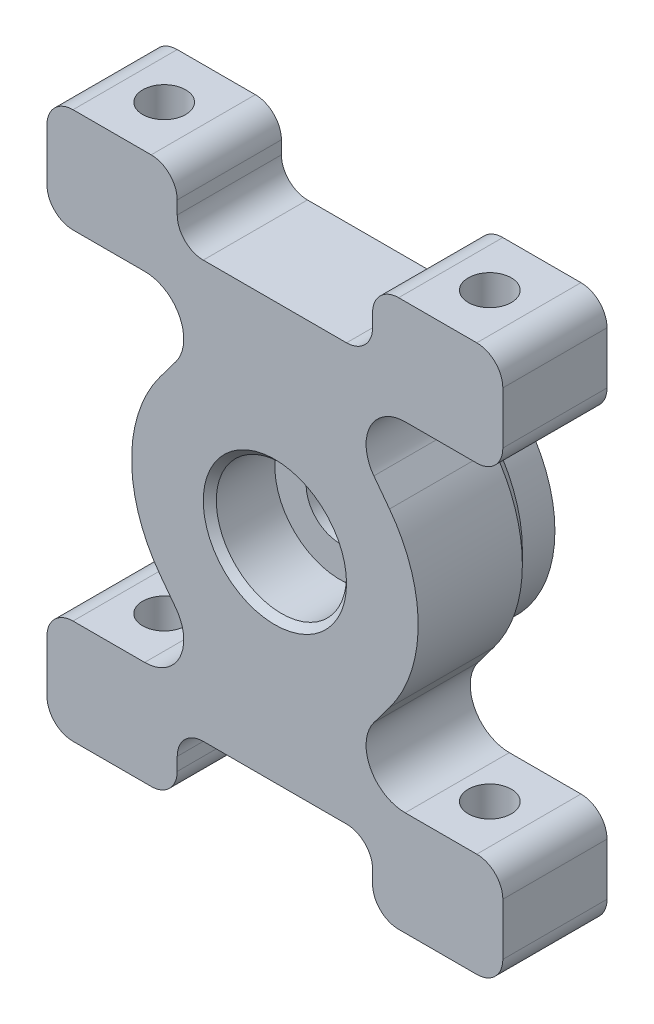
SolidWorks part; units mm, degrees
material "6061 合金"
ref_plane "前视基准面" through (0, 0, 0) normal (0, 0, 1) x (1, 0, 0)
ref_plane "上视基准面" through (0, 0, 0) normal (0, 1, 0) x (1, 0, 0)
ref_plane "右视基准面" through (0, 0, 0) normal (1, 0, 0) x (0, 0, -1)
sketch "草图1" plane through (0, 0, 0) normal (0, 0, 1) x (1, 0, 0)
  line L1 (-17.5, 21) -> (17.5, 21)
  line L2 (-17.5, 21) -> (-17.5, -21)
  line L3 (-17.5, -21) -> (17.5, -21)
  line L4 (17.5, 21) -> (17.5, -21)
  line L5 (-17.5, 21) -> (17.5, -21) construction
  line L6 (-17.5, -21) -> (17.5, 21) construction
  point P0 (0, 0)
  dimension "D1" = 42
  dimension "D2" = 35
extrude "凸台-拉伸1" add sketch "草图1" along normal mid plane 8
sketch "草图3" plane through (0, 21, 0) normal (0, 1, 0) x (1, 0, 0)
  line L0 (-12.5, 0) -> (12.5, 0) construction
  point P3 (0, 0)
  dimension "D1" = 25
sketch "草图4" plane through (0, 0, -4) normal (0, 0, -1) x (-1, 0, 0)
  line L1 (-5, 6) -> (5, 6)
  line L2 (-6, 5) -> (-6, -5)
  line L3 (-5, -6) -> (5, -6)
  line L4 (6, 5) -> (6, -5)
  line L5 (-6, 6) -> (6, -6) construction
  line L6 (-6, -6) -> (6, 6) construction
  circle A0 centre (0, 0) radius 10
  arc A1 (5, 6) -> (6, 5) centre (5, 5) cw
  arc A2 (5, -6) -> (6, -5) centre (5, -5) ccw
  arc A3 (-6, -5) -> (-5, -6) centre (-5, -5) ccw
  arc A4 (-5, 6) -> (-6, 5) centre (-5, 5) ccw
  dimension "D2" = 1
  dimension "D3" = 20
  dimension "D1" = 12
extrude "凸台-拉伸2" add sketch "草图4" along normal blind 3.5
sketch "草图5" plane through (0, 0, -4) normal (0, 0, -1) x (-1, 0, 0)
  line L4 (6, -5) -> (6, 5)
  line L5 (5, 6) -> (-5, 6)
  line L6 (-6, 5) -> (-6, -5)
  line L7 (-5, -6) -> (5, -6)
  line L8 (6, -5) -> (6, 5)
  line L9 (5, 6) -> (-5, 6)
  line L10 (-6, 5) -> (-6, -5)
  line L11 (-5, -6) -> (5, -6)
  arc A4 (6, 5) -> (5, 6) centre (5, 5) ccw
  arc A5 (-5, 6) -> (-6, 5) centre (-5, 5) ccw
  arc A6 (-6, -5) -> (-5, -6) centre (-5, -5) ccw
  arc A7 (5, -6) -> (6, -5) centre (5, -5) ccw
  arc A8 (6, 5) -> (5, 6) centre (5, 5) ccw
  arc A9 (-5, 6) -> (-6, 5) centre (-5, 5) ccw
  arc A10 (-6, -5) -> (-5, -6) centre (-5, -5) ccw
  arc A11 (5, -6) -> (6, -5) centre (5, -5) ccw
  dimension "D1" = 0
extrude "切除-拉伸2" cut sketch "草图5" against normal blind 2
sketch "草图6" plane through (0, 0, 4) normal (0, 0, 1) x (1, 0, 0)
  circle A0 centre (0, 0) radius 2.6
  dimension "D1" = 5.2
extrude "切除-拉伸3" cut sketch "草图6" against normal through all
sketch "草图7" plane through (0, 0, 4) normal (0, 0, 1) x (1, 0, 0)
  circle A0 centre (0, 0) radius 5
  dimension "D1" = 10
extrude "切除-拉伸4" cut sketch "草图7" against normal blind 5
chamfer "倒角1" distance 0.5 angle 45 8 edges at (0, 6, -7.5) (5.7071, 5.7071, -7.5) (-5.7071, 5.7071, -7.5) (6, 0, -7.5) (-6, 0, -7.5) (5.7071, -5.7071, -7.5) (-5.7071, -5.7071, -7.5) (0, -6, -7.5)
chamfer "倒角2" distance 0.5 angle 45 1 edges at (5, 0, 4)
chamfer "倒角3" distance 1 angle 45 1 edges at (10, 0, -4)
sketch "草图10" plane through (0, 0, 4) normal (0, 0, 1) x (1, 0, 0)
  line L0 (17.5, -21) -> (17.5, 21) construction
  line L1 (17.5, -13) -> (11, -13)
  line L2 (17.5, -13) -> (17.5, 13)
  line L3 (17.5, 13) -> (11, 13)
  line L4 (11, -13) -> (11, 13)
  line L5 (-17.5, -21) -> (17.5, -21) construction
  line L6 (17.5, 21) -> (-17.5, 21) construction
  line L7 (11, 13) -> (4, 13)
  line L8 (4, 13) -> (8.8, 6.6)
  line L11 (11, -13) -> (4, -13)
  line L12 (4, -13) -> (8.8, -6.6)
  circle A0 centre (0, 0) radius 11 construction
  circle A1 centre (0, 0) radius 11
  line M6 (17.5, -21) -> (17.5, 21)
  dimension "D1" = 8
  dimension "D2" = 8
  dimension "D3" = 6.5
  dimension "D4" = 7
  dimension "D5" = 13.5
extrude "切除-拉伸5" cut sketch "草图10" against normal through all contours L4 L1 L3 M6 | A1 L4 L7 L8 | A1 L12 L11 L4
mirror "镜向1" about plane through (0, 0, 0) normal (1, 0, 0) of "切除-拉伸5"
fillet "圆角1" radius 3 4 edges at (4, 13, 0) (4, -13, 0) (-4, -13, 0) (-4, 13, 0)
hole_wizard "M4 螺纹孔1" positions "草图11" profile "草图13" tap size "M4" standard "ISO"
sketch "草图11" plane through (0, 21, 0) normal (0, 1, 0) x (1, 0, 0)
  point P0 (12.5, 0)
  point P3 (-12.5, 0)
sketch "草图13" plane through (12.5, 21, 0) normal (1, 0, 0) x (0, 0, 1)
  line L0 (0, 0) -> (0, 8)
  line L1 (0, 8) -> (1.65, 8)
  line L2 (1.65, 8) -> (1.65, 0)
  line L5 (1.65, 0) -> (0, 0)
  line L11 (0, -6.35) -> (0, 107.95) construction
  dimension "通孔螺纹孔钻头直径" = 3.3
  dimension "通孔螺纹孔钻头深度" = 8
cosmetic thread "孔螺蚊线1" parameters "D2"=4
cosmetic thread "孔螺蚊线2" parameters "D2"=4
mirror "镜向2" about plane through (0, 0, 0) normal (0, 1, 0) of "M4 螺纹孔1"
cosmetic thread "孔螺蚊线3" parameters "D2"=4
cosmetic thread "孔螺蚊线4" parameters "D2"=4
sketch "草图14" plane through (0, 0, -4) normal (0, 0, -1) x (-1, 0, 0)
  line L0 (17.5, -21) -> (-17.5, -21) construction
  line L1 (-7.5, 21) -> (7.5, 21)
  line L2 (-7.5, 21) -> (-7.5, -21)
  line L3 (-7.5, -21) -> (7.5, -21)
  line L4 (7.5, 21) -> (7.5, -21)
  line L5 (-7.5, 21) -> (7.5, -21) construction
  line L6 (-7.5, -21) -> (7.5, 21) construction
  line L8 (-7.5, 16) -> (7.5, 16)
  line L9 (-7.5, 16) -> (-7.5, -16)
  line L10 (-7.5, -16) -> (7.5, -16)
  line L11 (7.5, 16) -> (7.5, -16)
  line L12 (-7.5, 16) -> (7.5, -16) construction
  line L13 (-7.5, -16) -> (7.5, 16) construction
  point P0 (0, 0)
  point P8 (0, 0)
  line M9 (17.5, 21) -> (-17.5, 21)
  dimension "D1" = 32
  dimension "D2" = 15
extrude "切除-拉伸6" cut sketch "草图14" against normal through all contours L2 L8 L4 M9 | L10 L2 L3 L4
fillet "圆角2" radius 2 8 edges at (-17.5, 21, 0) (17.5, 21, 0) (17.5, 13, 0) (17.5, -13, 0) (17.5, -21, 0) (-17.5, -21, 0) (-17.5, -13, 0) (-17.5, 13, 0)
fillet "圆角3" radius 2 8 edges at (-7.5, 21, 0) (-7.5, 16, 0) (7.5, 16, 0) (7.5, -21, 0) (7.5, -16, 0) (-7.5, -16, 0) (-7.5, -21, 0) (7.5, 21, 0)
